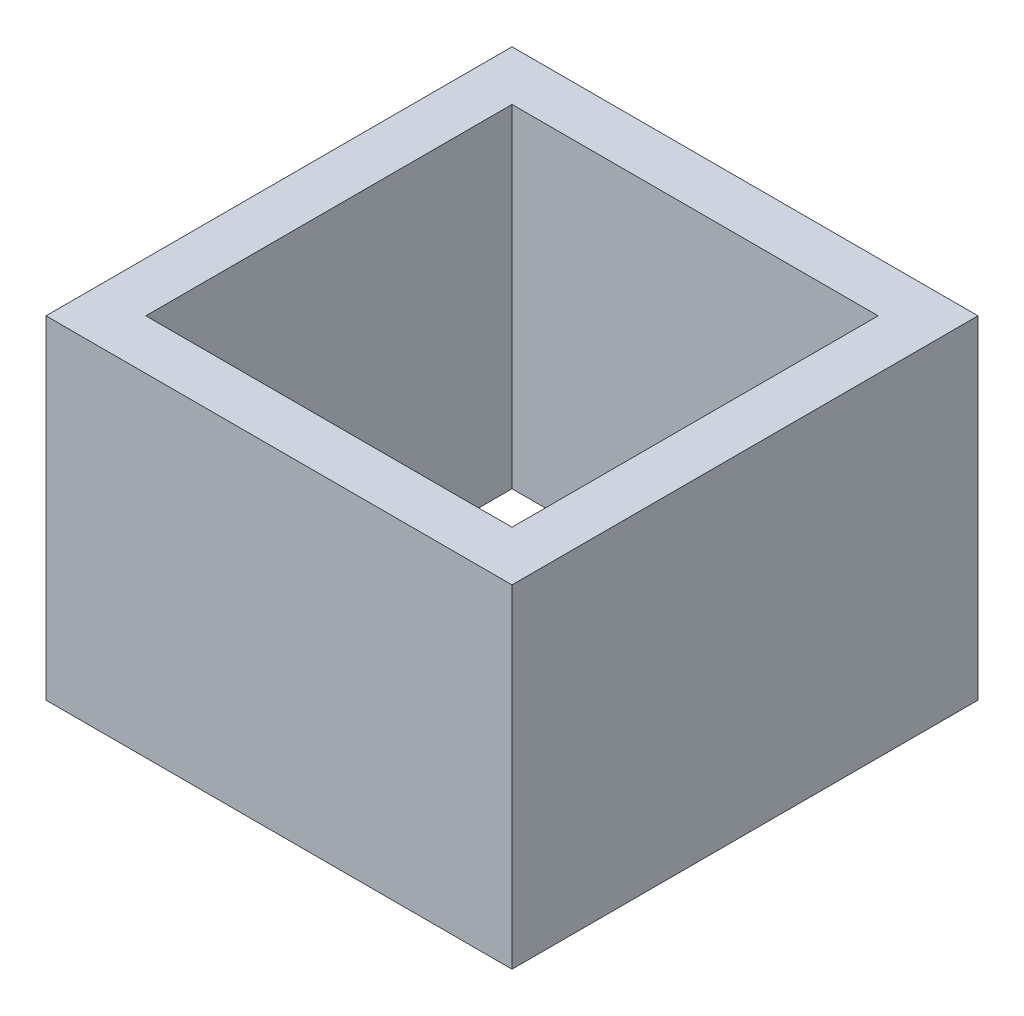
SolidWorks part; units mm, degrees
ref_plane "前视基准面" through (0, 0, 0) normal (0, 0, 1) x (1, 0, 0)
ref_plane "上视基准面" through (0, 0, 0) normal (0, 1, 0) x (1, 0, 0)
ref_plane "右视基准面" through (0, 0, 0) normal (1, 0, 0) x (0, 0, -1)
sketch "草图1" plane through (0, 0, 0) normal (0, 1, 0) x (1, 0, 0)
  line L1 (-25, -25) -> (25, -25)
  line L2 (-25, -25) -> (-25, 25)
  line L3 (-25, 25) -> (25, 25)
  line L4 (25, -25) -> (25, 25)
  line L5 (-25, -25) -> (25, 25) construction
  line L6 (-25, 25) -> (25, -25) construction
  line L7 (-35, -35) -> (35, -35)
  line L8 (-35, -35) -> (-35, 35)
  line L9 (-35, 35) -> (35, 35)
  line L10 (35, -35) -> (35, 35)
  line L11 (-35, -35) -> (35, 35) construction
  line L12 (-35, 35) -> (35, -35) construction
  point P0 (0, 0)
  point P6 (0, 0)
  dimension "D1" = 50
  dimension "D2" = 50
  dimension "D3" = 70
  dimension "D4" = 70
  dimension "D5" = 70
extrude "凸台-拉伸1" add sketch "草图1" against normal blind 50 contours L8 L9 L10 L7
sketch "草图2" plane through (0, 0, 0) normal (0, 1, 0) x (1, 0, 0)
  line L1 (-27.5, 27.5) -> (27.5, 27.5)
  line L2 (-27.5, 27.5) -> (-27.5, -27.5)
  line L3 (-27.5, -27.5) -> (27.5, -27.5)
  line L4 (27.5, 27.5) -> (27.5, -27.5)
  line L5 (-27.5, 27.5) -> (27.5, -27.5) construction
  line L6 (-27.5, -27.5) -> (27.5, 27.5) construction
  point P0 (0, 0)
  dimension "D1" = 55
  dimension "D2" = 55
extrude "切除-拉伸1" cut sketch "草图2" against normal blind 50
